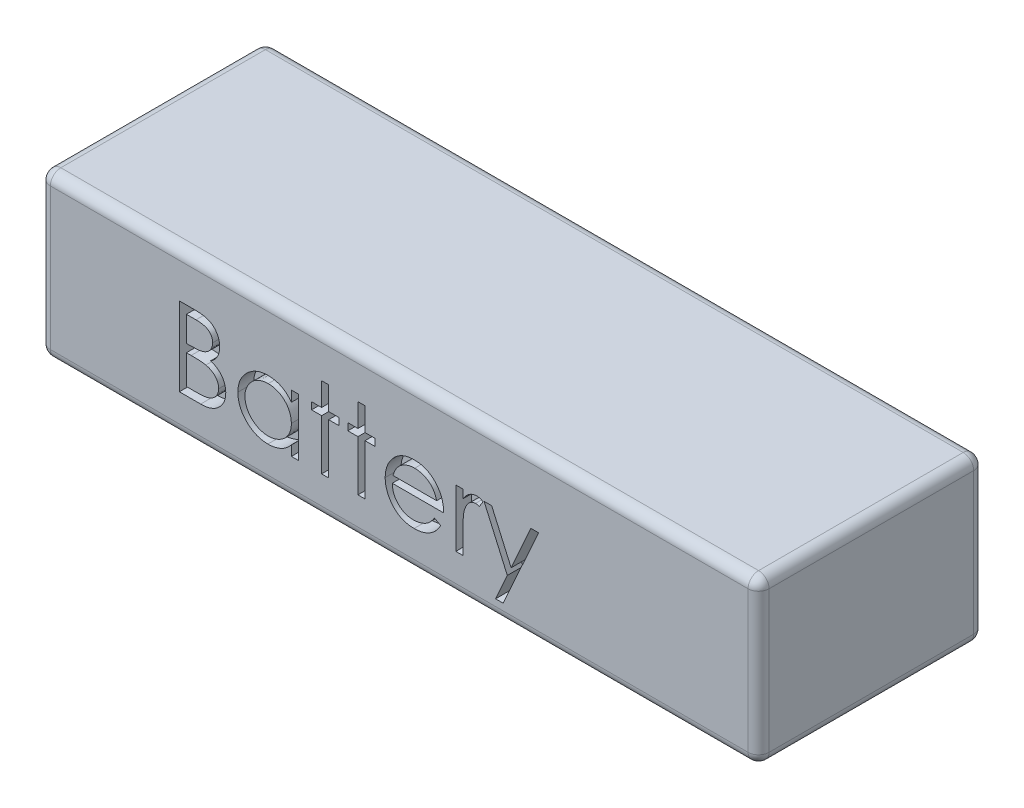
SolidWorks part; units mm, degrees
material "Custom Plastic"
ref_plane "Front Plane" through (0, 0, 0) normal (0, 0, 1) x (1, 0, 0)
ref_plane "Top Plane" through (0, 0, 0) normal (0, 1, 0) x (1, 0, 0)
ref_plane "Right Plane" through (0, 0, 0) normal (1, 0, 0) x (0, 0, -1)
sketch "Sketch1" plane through (0, 0, 0) normal (0, 1, 0) x (1, 0, 0)
  line L1 (0, 0) -> (137, 0)
  line L2 (0, 0) -> (0, 43)
  line L3 (0, 43) -> (137, 43)
  line L4 (137, 0) -> (137, 43)
  dimension "D1" = 137
  dimension "D2" = 43
extrude "Boss-Extrude1" add sketch "Sketch1" along normal blind 31
sketch "Sketch3" plane through (0, 0, 0) normal (0, 0, 1) x (1, 0, 0)
  text T0 "Battery" font "Century Gothic" height 15
extrude "Cut-Extrude1" cut sketch "Sketch3" against normal blind 3
sketch "Sketch4" plane through (0, 0, -43) normal (0, 0, -1) x (-1, 0, 0)
  text T0 "Battery" font "Century Gothic" height 10
extrude "Cut-Extrude2" cut sketch "Sketch4" against normal blind 3
fillet "Fillet1" radius 2 12 edges at (137, 15.5, 0) (137, 15.5, -43) (0, 15.5, -43) (0, 15.5, 0) (68.5, 0, 0) (137, 0, -21.5) (68.5, 0, -43) (0, 0, -21.5) (68.5, 31, -43) (137, 31, -21.5) (68.5, 31, 0) (0, 31, -21.5)
ref_plane "Plane1" through (0, 0, -21.5) normal (0, 0, 1) x (1, 0, 0)
ref_plane "Plane2" through (68.5, 0, 0) normal (-1, 0, 0) x (0, 0, 1)
